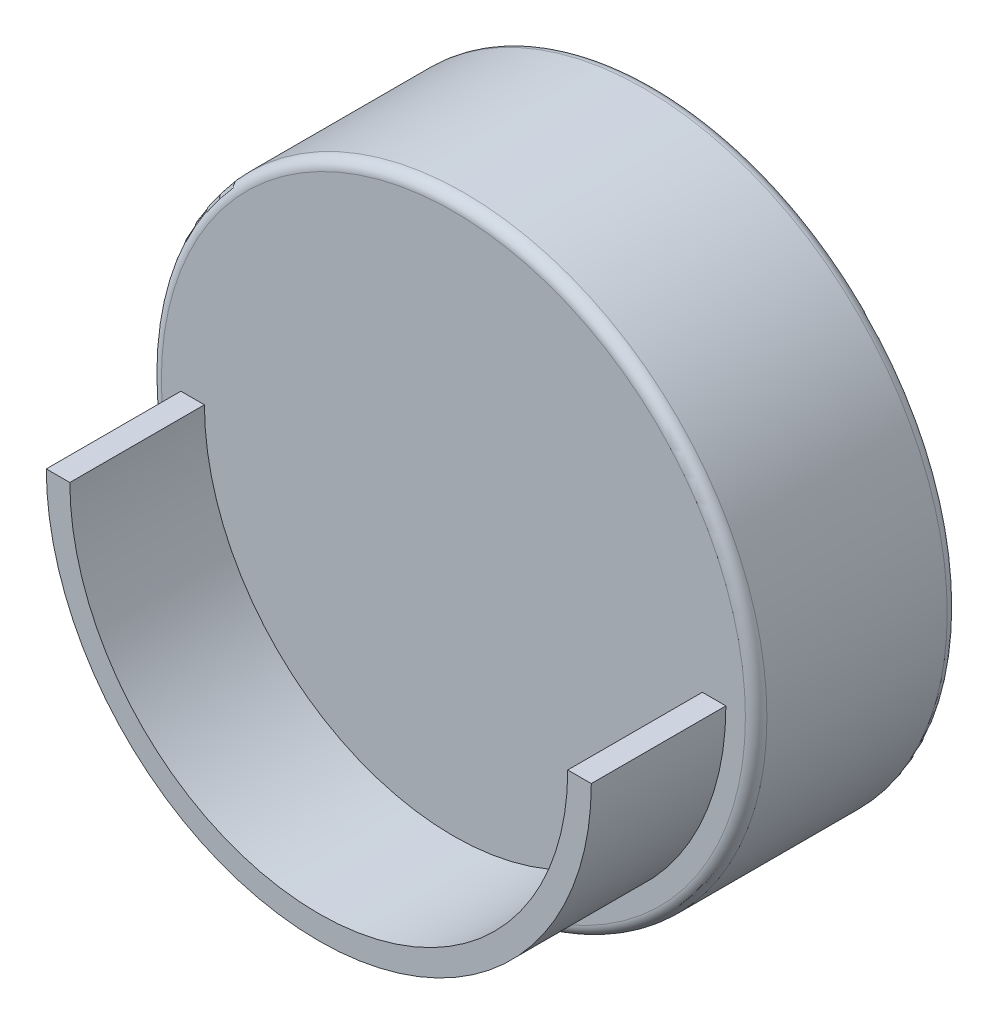
SolidWorks part; units mm, degrees
ref_plane "Front Plane" through (0, 0, 0) normal (0, 0, 1) x (1, 0, 0)
ref_plane "Top Plane" through (0, 0, 0) normal (0, 1, 0) x (1, 0, 0)
ref_plane "Right Plane" through (0, 0, 0) normal (1, 0, 0) x (0, 0, -1)
sketch "Sketch1" plane through (0, 0, 0) normal (0, 0, 1) x (1, 0, 0)
  circle A0 centre (0, 0) radius 22.5
  dimension "D1" = 45
extrude "Boss-Extrude1" add sketch "Sketch1" along normal blind 15
sketch "Sketch2" plane through (0, 0, 15) normal (0, 0, 1) x (1, 0, 0)
  circle A0 centre (0, 0) radius 20.25
  circle A1 centre (0, 0) radius 18.5
  dimension "D1" = 40.5
  dimension "D2" = 37
extrude "Boss-Extrude2" add sketch "Sketch2" along normal blind 10
sketch "Sketch4" plane through (0, 0, 0) normal (1, 0, 0) x (0, 0, -1)
  line L0 (-25, 20.25) -> (-25, -20.25) construction
  line L1 (-25, 0) -> (-15, 0)
  line L2 (-25, 0) -> (-25, 24.7521)
  line L3 (-25, 24.7521) -> (-15, 24.7521)
  line L4 (-15, 0) -> (-15, 24.7521)
extrude "Cut-Extrude1" cut sketch "Sketch4" against normal through all both and the other way through all
fillet "Fillet1" radius 0.8 2 edges at (22.5, 0, 0) (22.5, 0, 15)
sketch "Sketch5" plane through (0, 0, 0) normal (0, 0, -1) x (-1, 0, 0)
  circle A0 centre (0, 0) radius 20.25
  circle A1 centre (0, 0) radius 12.5
  dimension "D1" = 40.5
  dimension "D2" = 25
extrude "Cut-Extrude2" cut sketch "Sketch5" against normal blind 10
